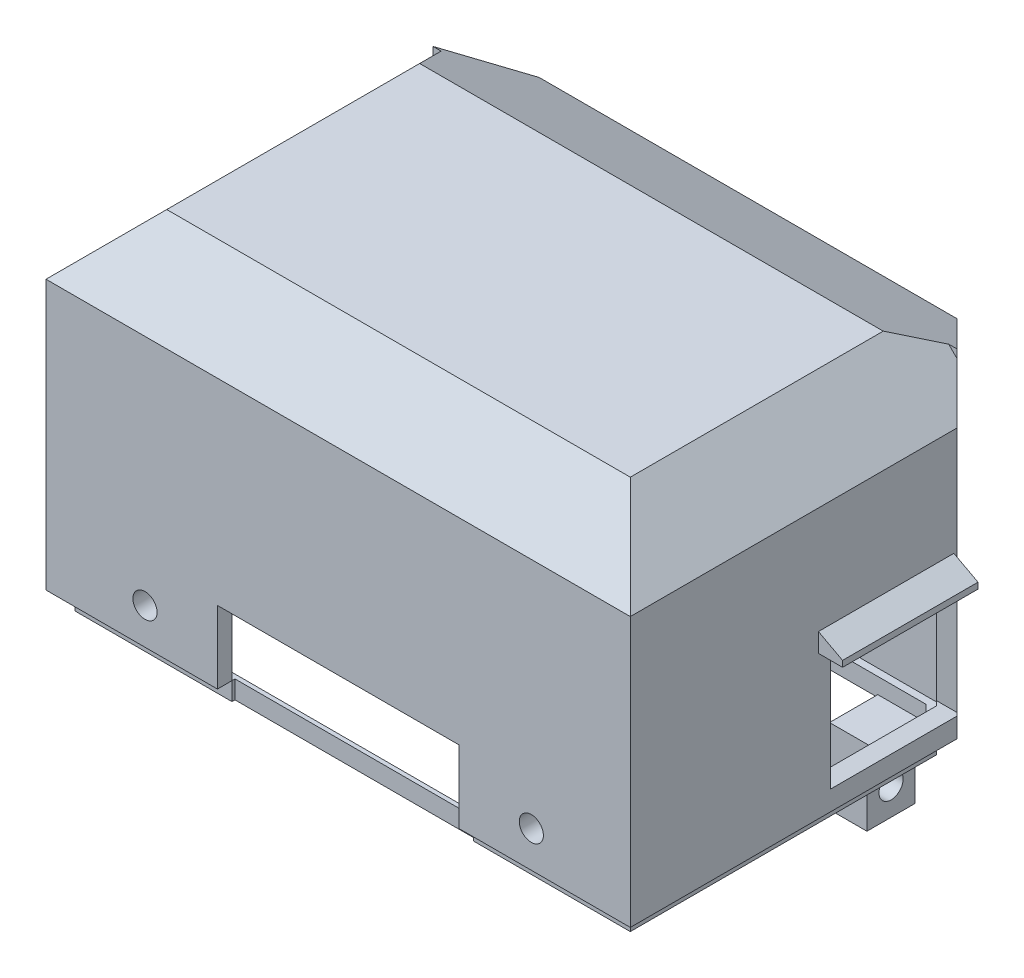
SolidWorks part; units mm, degrees
ref_plane "Front Plane" through (0, 0, 0) normal (0, 0, 1) x (1, 0, 0)
ref_plane "Top Plane" through (0, 0, 0) normal (0, 1, 0) x (1, 0, 0)
ref_plane "Right Plane" through (0, 0, 0) normal (1, 0, 0) x (0, 0, -1)
ref_plane "PXm48_4" through (-48.4, 0, 0) normal (1, 0, 0) x (0, 0, -1)
sketch "Sketch1" plane through (-48.4, 0, 0) normal (1, 0, 0) x (0, 0, -1)
  line L0 (-11.9, -4) -> (48.2, -4)
  line L1 (48.2, -4) -> (48.2, 46.4488)
  line L2 (48.2, 46.4488) -> (40, 50.6)
  line L3 (40, 50.6) -> (-1.9, 50.6)
  line L4 (-1.9, 50.6) -> (-11.9, 40.6)
  line L5 (-11.9, 40.6) -> (-11.9, -4)
extrude "Head Block" add sketch "Sketch1" along normal blind 96.8
sketch "Sketch2" plane through (0, 0, 0) normal (0, 0, 1) x (1, 0, 0)
  line L0 (-37.4, 51.6) -> (-49.4, 51.6)
  line L1 (-49.4, 51.6) -> (-49.4, 39.6)
  line L2 (-49.4, 39.6) -> (-37.4, 51.6)
extrude "Roof Corner Facet L" cut sketch "Sketch2" against normal through all and the other way through all
sketch "Sketch3" plane through (0, 0, 0) normal (0, 0, 1) x (1, 0, 0)
  line L0 (37.4, 51.6) -> (49.4, 51.6)
  line L1 (49.4, 51.6) -> (49.4, 39.6)
  line L2 (49.4, 39.6) -> (37.4, 51.6)
extrude "Roof Corner Facet R" cut sketch "Sketch3" against normal through all and the other way through all
sketch "Sketch4" plane through (0, 0, 0) normal (0, 1, 0) x (1, 0, 0)
  line L0 (-30.4, 60.2) -> (-49.4, 60.2)
  line L1 (-49.4, 60.2) -> (-49.4, 41.2)
  line L2 (-49.4, 41.2) -> (-30.4, 60.2)
extrude "Front Corner Facet L" cut sketch "Sketch4" against normal through all and the other way through all
sketch "Sketch5" plane through (0, 0, 0) normal (0, 1, 0) x (1, 0, 0)
  line L0 (30.4, 60.2) -> (49.4, 60.2)
  line L1 (49.4, 60.2) -> (49.4, 41.2)
  line L2 (49.4, 41.2) -> (30.4, 60.2)
extrude "Front Corner Facet R" cut sketch "Sketch5" against normal through all and the other way through all
shell "Shell" thickness 2.4
ref_plane "PXm47_9" through (-47.9, 0, 0) normal (1, 0, 0) x (0, 0, -1)
sketch "Sketch6" plane through (-47.9, 0, 0) normal (1, 0, 0) x (0, 0, -1)
  line L0 (47.2, 40) -> (56, 40)
  line L1 (56, 40) -> (56, 42.5)
  line L2 (56, 42.5) -> (47.2, 46.955)
  line L3 (47.2, 46.955) -> (47.2, 40)
extrude "Brow" add sketch "Sketch6" along normal blind 95.8
sketch "Sketch7" plane through (0, 0, 0) normal (0, 1, 0) x (1, 0, 0)
  line L0 (-30.4, 60.2) -> (-49.4, 60.2)
  line L1 (-49.4, 60.2) -> (-49.4, 41.2)
  line L2 (-49.4, 41.2) -> (-30.4, 60.2)
extrude "Brow Corner Facet L" cut sketch "Sketch7" against normal through all and the other way through all
sketch "Sketch8" plane through (0, 0, 0) normal (0, 1, 0) x (1, 0, 0)
  line L0 (30.4, 60.2) -> (49.4, 60.2)
  line L1 (49.4, 60.2) -> (49.4, 41.2)
  line L2 (49.4, 41.2) -> (30.4, 60.2)
extrude "Brow Corner Facet R" cut sketch "Sketch8" against normal through all and the other way through all
ref_plane "PYm54_5" through (0, 0, -54.5) normal (0, 0, 1) x (1, 0, 0)
sketch "Sketch9" plane through (0, 0, -54.5) normal (0, 0, 1) x (1, 0, 0)
  line L0 (-46.4, 39.99) -> (46.4, 39.99)
  line L1 (46.4, 39.99) -> (46.4, 40.8)
  line L2 (46.4, 40.8) -> (-46.4, 40.8)
  line L3 (-46.4, 40.8) -> (-46.4, 39.99)
extrude "Brow Drip Groove" cut sketch "Sketch9" along normal blind 1
ref_plane "PZm7" through (0, -7, 0) normal (0, 1, 0) x (1, 0, 0)
sketch "Sketch10" plane through (0, -7, 0) normal (0, 1, 0) x (1, 0, 0)
  line L0 (-46, -9.5) -> (46, -9.5)
  line L1 (46, -9.5) -> (46, 41.2059)
  line L2 (46, 41.2059) -> (41.4059, 45.8)
  line L3 (41.4059, 45.8) -> (-41.4059, 45.8)
  line L4 (-41.4059, 45.8) -> (-46, 41.2059)
  line L5 (-46, 41.2059) -> (-46, -9.5)
  line L6 (-44.8, -8.3) -> (44.8, -8.3)
  line L7 (44.8, -8.3) -> (44.8, 40.7088)
  line L8 (44.8, 40.7088) -> (40.9088, 44.6)
  line L9 (40.9088, 44.6) -> (-40.9088, 44.6)
  line L10 (-40.9088, 44.6) -> (-44.8, 40.7088)
  line L11 (-44.8, 40.7088) -> (-44.8, -8.3)
extrude "Seam Skirt" add sketch "Sketch10" along normal blind 3.01
ref_plane "PZm12_5" through (0, -12.5, 0) normal (0, 1, 0) x (1, 0, 0)
sketch "Sketch11" plane through (0, -12.5, 0) normal (0, 1, 0) x (1, 0, 0)
  line L0 (-45.7, 30) -> (-39.5, 30)
  line L1 (-39.5, 30) -> (-39.5, 38)
  line L2 (-39.5, 38) -> (-45.7, 38)
  line L3 (-45.7, 38) -> (-45.7, 30)
extrude "Seam Block L" add sketch "Sketch11" along normal blind 8.5
ref_plane "PZm4_01" through (0, -4.01, 0) normal (0, 1, 0) x (1, 0, 0)
sketch "Sketch12" plane through (0, -4.01, 0) normal (0, 1, 0) x (1, 0, 0)
  line L0 (-46.2, 30) -> (-39.5, 30)
  line L1 (-39.5, 30) -> (-39.5, 38)
  line L2 (-39.5, 38) -> (-46.2, 38)
  line L3 (-46.2, 38) -> (-46.2, 30)
extrude "Seam Block Root L" add sketch "Sketch12" along normal blind 4.01
ref_plane "PXm45_8" through (-45.8, 0, 0) normal (1, 0, 0) x (0, 0, -1)
sketch "Sketch13" plane through (-45.8, 0, 0) normal (1, 0, 0) x (0, 0, -1)
  circle A0 centre (34, -8) radius 2
extrude "Seam Insert L" cut sketch "Sketch13" along normal blind 6.1
sketch "Sketch14" plane through (0, -12.5, 0) normal (0, 1, 0) x (1, 0, 0)
  line L0 (39.5, 30) -> (45.7, 30)
  line L1 (45.7, 30) -> (45.7, 38)
  line L2 (45.7, 38) -> (39.5, 38)
  line L3 (39.5, 38) -> (39.5, 30)
extrude "Seam Block R" add sketch "Sketch14" along normal blind 8.5
sketch "Sketch15" plane through (0, -4.01, 0) normal (0, 1, 0) x (1, 0, 0)
  line L0 (39.5, 30) -> (46.2, 30)
  line L1 (46.2, 30) -> (46.2, 38)
  line L2 (46.2, 38) -> (39.5, 38)
  line L3 (39.5, 38) -> (39.5, 30)
extrude "Seam Block Root R" add sketch "Sketch15" along normal blind 4.01
ref_plane "PX39_7" through (39.7, 0, 0) normal (1, 0, 0) x (0, 0, -1)
sketch "Sketch16" plane through (39.7, 0, 0) normal (1, 0, 0) x (0, 0, -1)
  circle A0 centre (34, -8) radius 2
extrude "Seam Insert R" cut sketch "Sketch16" along normal blind 6.1
ref_plane "PY9" through (0, 0, 9) normal (0, 0, 1) x (1, 0, 0)
sketch "Sketch17" plane through (0, 0, 9) normal (0, 0, 1) x (1, 0, 0)
  line L0 (-20, -8) -> (20, -8)
  line L1 (20, -8) -> (20, 8)
  line L2 (20, 8) -> (-20, 8)
  line L3 (-20, 8) -> (-20, -8)
extrude "Cable Window" cut sketch "Sketch17" along normal blind 3.9
ref_plane "PY3_5" through (0, 0, 3.5) normal (0, 0, 1) x (1, 0, 0)
sketch "Sketch18" plane through (0, 0, 3.5) normal (0, 0, 1) x (1, 0, 0)
  circle A0 centre (-32, 2) radius 4
  circle A1 centre (32, 2) radius 4
extrude "Flange Bosses" add sketch "Sketch18" along normal blind 6.2
ref_plane "PY5_4" through (0, 0, 5.4) normal (0, 0, 1) x (1, 0, 0)
sketch "Sketch19" plane through (0, 0, 5.4) normal (0, 0, 1) x (1, 0, 0)
  circle A0 centre (-32, 2) radius 2
  circle A1 centre (32, 2) radius 2
extrude "Flange Insert Holes" cut sketch "Sketch19" along normal blind 7
ref_plane "PZ17" through (0, 17, 0) normal (0, 1, 0) x (1, 0, 0)
sketch "Sketch20" plane through (0, 17, 0) normal (0, 1, 0) x (1, 0, 0)
  line L0 (-18.9, 29.3) -> (-14.9, 29.3)
  line L1 (-14.9, 29.3) -> (-14.9, 46.3)
  line L2 (-14.9, 46.3) -> (-18.9, 46.3)
  line L3 (-18.9, 46.3) -> (-18.9, 29.3)
extrude "Camera Rail L" add sketch "Sketch20" along normal blind 29
sketch "Sketch21" plane through (0, 17, 0) normal (0, 1, 0) x (1, 0, 0)
  line L0 (-15.4, 29.3) -> (-12.9, 29.3)
  line L1 (-12.9, 29.3) -> (-12.9, 30.35)
  line L2 (-12.9, 30.35) -> (-15.4, 30.35)
  line L3 (-15.4, 30.35) -> (-15.4, 29.3)
extrude "Camera Rear Lip L" add sketch "Sketch21" along normal blind 27.2
sketch "Sketch22" plane through (0, 17, 0) normal (0, 1, 0) x (1, 0, 0)
  line L0 (14.9, 29.3) -> (18.9, 29.3)
  line L1 (18.9, 29.3) -> (18.9, 46.3)
  line L2 (18.9, 46.3) -> (14.9, 46.3)
  line L3 (14.9, 46.3) -> (14.9, 29.3)
extrude "Camera Rail R" add sketch "Sketch22" along normal blind 29
sketch "Sketch23" plane through (0, 17, 0) normal (0, 1, 0) x (1, 0, 0)
  line L0 (12.9, 29.3) -> (15.4, 29.3)
  line L1 (15.4, 29.3) -> (15.4, 30.35)
  line L2 (15.4, 30.35) -> (12.9, 30.35)
  line L3 (12.9, 30.35) -> (12.9, 29.3)
extrude "Camera Rear Lip R" add sketch "Sketch23" along normal blind 27.2
ref_plane "PZ45_5" through (0, 45.5, 0) normal (0, 1, 0) x (1, 0, 0)
sketch "Sketch24" plane through (0, 45.5, 0) normal (0, 1, 0) x (1, 0, 0)
  line L0 (-18.9, 34) -> (18.9, 34)
  line L1 (18.9, 34) -> (18.9, 38)
  line L2 (18.9, 38) -> (-18.9, 38)
  line L3 (-18.9, 38) -> (-18.9, 34)
extrude "Camera Top Bar" add sketch "Sketch24" along normal blind 1.5
ref_plane "PZ16_5" through (0, 16.5, 0) normal (0, 1, 0) x (1, 0, 0)
sketch "Sketch25" plane through (0, 16.5, 0) normal (0, 1, 0) x (1, 0, 0)
  circle A0 centre (-16.9, 31) radius 0.8
  circle A1 centre (-16.9, 43.5) radius 0.8
  circle A2 centre (16.9, 31) radius 0.8
  circle A3 centre (16.9, 43.5) radius 0.8
extrude "Retainer Pilots" cut sketch "Sketch25" along normal blind 7.5
sketch "Sketch26" plane through (0, 0, 0) normal (0, 1, 0) x (1, 0, 0)
  line L0 (0, 33) -> (0, 43)
ref_plane "Plane15" through (0, 0, -43) normal (0, 0, -1) x (-1, 0, 0)
sketch "Sketch28" plane through (0, 0, -43) normal (0, 0, -1) x (-1, 0, 0)
  line L0 (4.8, 23.8) -> (-4.8, 23.8)
  line L1 (-4.8, 23.8) -> (-4.8, 33.4)
  line L2 (-4.8, 33.4) -> (4.8, 33.4)
  line L3 (4.8, 33.4) -> (4.8, 23.8)
extrude "Camera Window" cut sketch "Sketch28" along normal blind 6.7 draft 29.75 draft outward yes
sketch "Sketch29" plane through (0, 0, 0) normal (0, 1, 0) x (1, 0, 0)
  line L0 (-14.5, 32) -> (-24.5, 32)
ref_plane "Plane16" through (-24.5, 0, -32) normal (-1, 0, 0) x (0, 0, 1)
sketch "Sketch31" plane through (-24.5, 0, -32) normal (-1, 0, 0) x (0, 0, 1)
  line L0 (3.2, 6.8) -> (-3.2, 6.8)
  line L1 (-3.2, 6.8) -> (-3.2, 11.2)
  line L2 (-3.2, 11.2) -> (3.2, 11.2)
  line L3 (3.2, 11.2) -> (3.2, 6.8)
extrude "ToF Window Left" cut sketch "Sketch31" along normal blind 25.4 draft 17.5
sketch "Sketch32" plane through (0, 0, 0) normal (0, 1, 0) x (1, 0, 0)
  line L0 (0, 33) -> (0, 43)
ref_plane "Plane17" through (0, 0, -43) normal (0, 0, -1) x (-1, 0, 0)
sketch "Sketch34" plane through (0, 0, -43) normal (0, 0, -1) x (-1, 0, 0)
  line L0 (3.2, 6.8) -> (-3.2, 6.8)
  line L1 (-3.2, 6.8) -> (-3.2, 11.2)
  line L2 (-3.2, 11.2) -> (3.2, 11.2)
  line L3 (3.2, 11.2) -> (3.2, 6.8)
extrude "ToF Window Ahead" cut sketch "Sketch34" along normal blind 6.7 draft 17.5 draft outward yes
sketch "Sketch35" plane through (0, 0, 0) normal (0, 1, 0) x (1, 0, 0)
  line L0 (14.5, 32) -> (24.5, 32)
ref_plane "Plane18" through (24.5, 0, -32) normal (1, 0, 0) x (0, 0, -1)
sketch "Sketch37" plane through (24.5, 0, -32) normal (1, 0, 0) x (0, 0, -1)
  line L0 (3.2, 6.8) -> (-3.2, 6.8)
  line L1 (-3.2, 6.8) -> (-3.2, 11.2)
  line L2 (-3.2, 11.2) -> (3.2, 11.2)
  line L3 (3.2, 11.2) -> (3.2, 6.8)
extrude "ToF Window Right" cut sketch "Sketch37" along normal blind 25.4 draft 17.5
ref_plane "PXm13" through (-13, 0, 0) normal (1, 0, 0) x (0, 0, -1)
sketch "Sketch38" plane through (-13, 0, 0) normal (1, 0, 0) x (0, 0, -1)
  line L0 (47.7, 14) -> (54.2, 14)
  line L1 (54.2, 14) -> (54.2, 15)
  line L2 (54.2, 15) -> (47.7, 18.6)
  line L3 (47.7, 18.6) -> (47.7, 14)
extrude "ToF Hood Ahead" add sketch "Sketch38" along normal blind 26
ref_plane "PYm41_7" through (0, 0, -41.7) normal (0, 0, 1) x (1, 0, 0)
sketch "Sketch39" plane through (0, 0, -41.7) normal (0, 0, 1) x (1, 0, 0)
  line L0 (-47.9, 19.7356) -> (-52.4, 19.7356)
  line L1 (-52.4, 19.7356) -> (-52.4, 20.7356)
  line L2 (-52.4, 20.7356) -> (-47.9, 23.1356)
  line L3 (-47.9, 23.1356) -> (-47.9, 19.7356)
extrude "ToF Hood Left" add sketch "Sketch39" along normal blind 22.4356
sketch "Sketch40" plane through (0, 0, -41.7) normal (0, 0, 1) x (1, 0, 0)
  line L0 (47.9, 19.7356) -> (52.4, 19.7356)
  line L1 (52.4, 19.7356) -> (52.4, 20.7356)
  line L2 (52.4, 20.7356) -> (47.9, 23.1356)
  line L3 (47.9, 23.1356) -> (47.9, 19.7356)
extrude "ToF Hood Right" add sketch "Sketch40" along normal blind 22.4356
ref_plane "PYm49_2" through (0, 0, -49.2) normal (0, 0, 1) x (1, 0, 0)
sketch "Sketch41" plane through (0, 0, -49.2) normal (0, 0, 1) x (1, 0, 0)
  line L0 (-49.4, 1.5) -> (49.4, 1.5)
  line L1 (49.4, 1.5) -> (49.4, 3.5)
  line L2 (49.4, 3.5) -> (-49.4, 3.5)
  line L3 (-49.4, 3.5) -> (-49.4, 1.5)
extrude "Light-Bar Groove" cut sketch "Sketch41" along normal blind 2
ref_plane "PY5_5" through (0, 0, 5.5) normal (0, 0, 1) x (1, 0, 0)
sketch "Sketch42" plane through (0, 0, 5.5) normal (0, 0, 1) x (1, 0, 0)
  line L0 (-8, 11) -> (8, 11)
  line L1 (8, 11) -> (8, 17)
  line L2 (8, 17) -> (-8, 17)
  line L3 (-8, 17) -> (-8, 11)
extrude "Ribbon Tie Anchor" add sketch "Sketch42" along normal blind 4.2
ref_plane "PXm9" through (-9, 0, 0) normal (1, 0, 0) x (0, 0, -1)
sketch "Sketch43" plane through (-9, 0, 0) normal (1, 0, 0) x (0, 0, -1)
  line L0 (-9, 12) -> (-7, 12)
  line L1 (-7, 12) -> (-7, 16)
  line L2 (-7, 16) -> (-9, 16)
  line L3 (-9, 16) -> (-9, 12)
extrude "Ribbon Tie Slot" cut sketch "Sketch43" along normal blind 18
equation "\"BOARD_REAR\" = 86.0"
equation "\"BOARD_FRONT\" = 41.0"
equation "\"BOARD_END\" = 22.0"
equation "\"BOARD_ANGLED\" = 30.0"
equation "\"BOARD_DEPTH\" = 41.8431"
equation "\"PCB_T\" = 1.6"
equation "\"ABOVE_PCB\" = 14.0"
equation "\"BELOW_PCB\" = 6.0"
equation "\"MID_PARTS_H\" = 9.0"
equation "\"BOARD_HOLE_PILOT\" = 1.6"
equation "\"J2_X\" = 19.0"
equation "\"DUPONT_DROP\" = 14.0"
equation "\"BEND_R\" = 5.0"
equation "\"BOARD_GAP\" = 3.0"
equation "\"TOF_FOV\" = 25.0"
equation "\"TOF_MARGIN_DEG\" = 5.0"
equation "\"TOF_WIN_MARGIN\" = 1.0"
equation "\"TOF_Z\" = 9.0"
equation "\"TOF_SIDE_BEARING\" = 90.0"
equation "\"TOF_CONE_LEN\" = 70.0"
equation "\"CAM_W\" = 29.2"
equation "\"CAM_H\" = 28.2"
equation "\"CAM_D\" = 12.35"
equation "\"CAM_FRONT_Y\" = 43.0"
equation "\"CAM_BOTTOM_Z\" = 17.0"
equation "\"CAM_LENS_UP\" = 11.6"
equation "\"CAM_LENS_OPEN\" = 9.6"
equation "\"CAM_HFOV\" = 53.5"
equation "\"CAM_VFOV\" = 41.41"
equation "\"CAM_FOV_MARGIN\" = 3.0"
equation "\"CAM_FIT\" = 0.3"
equation "\"RIBBON_W\" = 16.0"
equation "\"RIBBON_T\" = 0.3"
equation "\"RIBBON_LEN\" = 150.0"
equation "\"RIBBON_EXIT_Y\" = 35.0"
equation "\"WALL\" = 2.4"
equation "\"HEAD_X\" = 48.4"
equation "\"HEAD_REAR_Y\" = -11.9"
equation "\"CAM_FOAM\" = 2.8"
equation "\"HEAD_FRONT_Y\" = 48.2"
equation "\"HEAD_TOP_Z\" = 50.6"
equation "\"HEAD_BOT_Z\" = -28.4"
equation "\"HEAD_SPLIT_Z\" = -4.0"
equation "\"SKIRT_T\" = 1.2"
equation "\"SKIRT_H\" = 3.0"
equation "\"SKIRT_FIT\" = 0.3"
equation "\"VISOR\" = 7.8"
equation "\"VISOR_Z\" = 40.0"
equation "\"ROOF_SLOPE_Y\" = 40.0"
equation "\"ROOF_CHAMFER\" = 10.0"
equation "\"REAR_CHAMFER\" = 10.0"
equation "\"CORNER_CHAMFER\" = 6.0"
equation "\"LOWER_SIDE_FACET\" = 6.0"
equation "\"LIGHTBAR_DEPTH\" = 1.0"
equation "\"HOOD_Z\" = 14.0"
equation "\"HOOD_L\" = 6.0"
equation "\"SIDE_HOOD_L\" = 4.0"
equation "\"INSERT_M3_D\" = 4.0"
equation "\"INSERT_M3_L\" = 6.0"
equation "\"M3_CLEAR\" = 3.4"
equation "\"M2_PILOT\" = 1.6"
equation "\"M25_PILOT\" = 2.2"
equation "\"BOX_X\" = 72.4"
equation "\"BOX_FRONT_Y\" = -11.9"
equation "\"BOX_REAR_Y\" = -154.4"
equation "\"BOX_BOT_Z\" = -28.4"
equation "\"BOX_TOP_Z\" = 10.0"
equation "\"LID_T\" = 2.4"
equation "\"LID_SKIRT\" = 1.6"
equation "\"LID_TONGUE_H\" = 3.0"
equation "\"LID_FIT\" = 0.3"
equation "\"GNSS_WIN_T\" = 1.2"
equation "\"DIVIDER_Y\" = -86.0"
equation "\"PI_X0\" = -40.0"
equation "\"PI_X1\" = 45.0"
equation "\"PI_Y1\" = -26.3"
equation "\"PI_Y0\" = -82.3"
equation "\"PI_STANDOFF\" = 8.0"
equation "\"ESP_X0\" = -46.0"
equation "\"ESP_Y0\" = -149.0"
equation "\"ESP_L\" = 75.0"
equation "\"ESP_W\" = 52.0"
equation "\"ESP_STANDOFF\" = 12.0"
equation "\"VENT_UPSTAND\" = 3.0"
equation "\"TUBE_D\" = 22.2"
equation "\"TUBE_LINER\" = 1.0"
equation "\"MOUNT_Y\" = -70.0"
equation "\"RAIL_W\" = 30.0"
equation "\"RAIL_W2\" = 38.0"
equation "\"RAIL_H\" = 6.0"
equation "\"SLIDE\" = 0.3"
equation "\"STOP_T\" = 6.0"
equation "\"CLAMP_W\" = 40.0"
equation "\"CLAMP_HALF\" = 20.0"
equation "\"CLAMP_DROP\" = 12.0"
equation "\"CAP_T\" = 12.0"
equation "\"CLAMP_BOLT_OFF\" = 16.6"
equation "\"M5_INSERT_D\" = 6.4"
equation "\"M5_CLEAR\" = 5.5"
equation "\"LOCK_D\" = 3.3"
equation "\"POD_TILT_DEG\" = 0.0"
equation "\"PRINT_LIMIT\" = 180.0"
